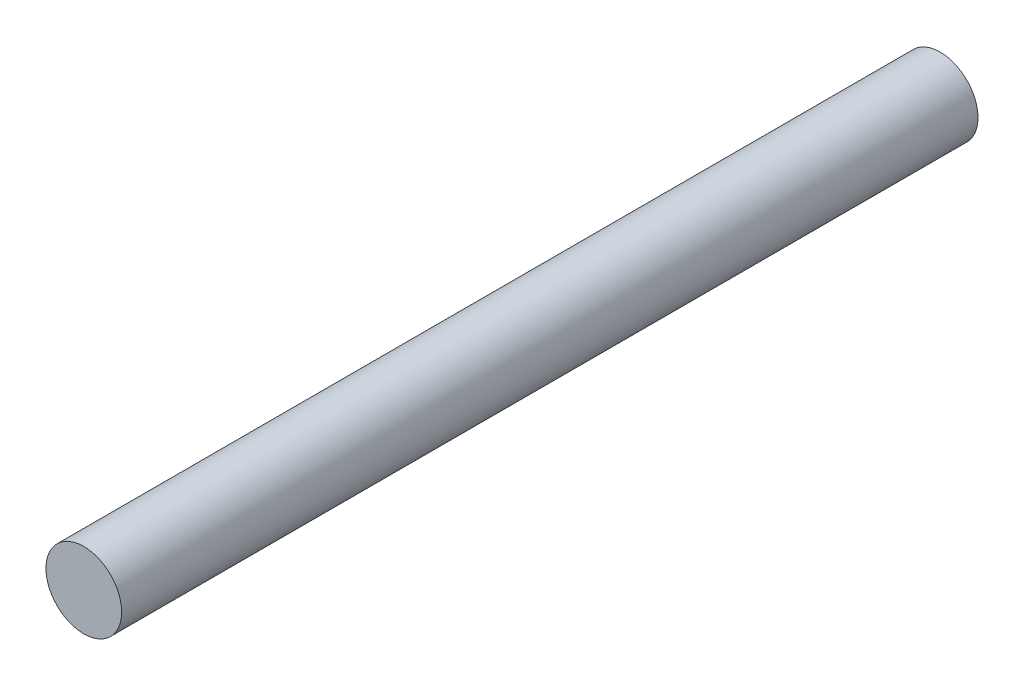
SolidWorks part; units mm, degrees
ref_plane "Front Plane" through (0, 0, 0) normal (0, 0, 1) x (1, 0, 0)
ref_plane "Top Plane" through (0, 0, 0) normal (0, 1, 0) x (1, 0, 0)
ref_plane "Right Plane" through (0, 0, 0) normal (1, 0, 0) x (0, 0, -1)
sketch "Sketch1" plane through (0, 0, 0) normal (0, 0, 1) x (1, 0, 0)
  circle A0 centre (0, 0) radius 4.8625
  dimension "D1" = 9.725
extrude "Boss-Extrude1" add sketch "Sketch1" along normal mid plane 110
